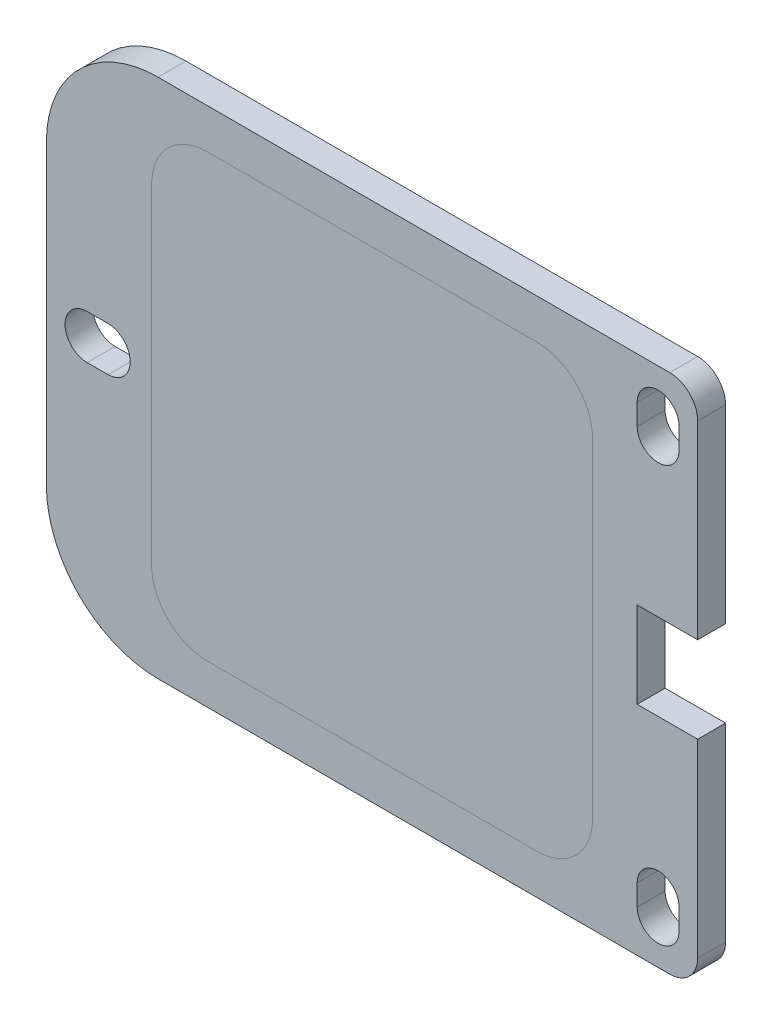
SolidWorks part; units mm, degrees
other "DetailItem1"
ref_plane "Front Plane" through (0, 0, 0) normal (0, 0, 1) x (1, 0, 0)
ref_plane "Top Plane" through (0, 0, 0) normal (0, 1, 0) x (1, 0, 0)
ref_plane "Right Plane" through (0, 0, 0) normal (1, 0, 0) x (0, 0, -1)
sketch "Sketch1" plane through (0, 0, 0) normal (0, 0, 1) x (1, 0, 0)
  line L0 (-222.25, 0) -> (180.975, 0) construction
  line L1 (-222.25, -177.8) -> (222.25, -177.8)
  line L2 (-222.25, -177.8) -> (-222.25, 177.8)
  line L3 (-222.25, 177.8) -> (222.25, 177.8)
  line L4 (222.25, -177.8) -> (222.25, -29.3687)
  line L5 (-222.25, -177.8) -> (222.25, 177.8) construction
  line L6 (-222.25, 177.8) -> (222.25, -177.8) construction
  line L7 (222.25, 29.3687) -> (180.975, 29.3687)
  line L8 (-194.4624, 0) -> (-180.1749, 0) construction
  line L9 (222.25, -29.3687) -> (180.975, -29.3687)
  line L10 (180.975, 29.3687) -> (180.975, -29.3687)
  line L11 (222.25, 29.3687) -> (222.25, 177.8)
  line L12 (-194.4624, 15.0812) -> (-180.1749, 15.0812)
  line L13 (-194.4624, -15.0812) -> (-180.1749, -15.0812)
  line L14 (195.2625, -134.9248) -> (195.2625, -149.225) construction
  line L15 (209.55, -134.9248) -> (209.55, -149.225)
  line L16 (180.975, -134.9248) -> (180.975, -149.225)
  line L17 (195.2625, 134.9248) -> (195.2625, 149.225) construction
  line L18 (209.55, 134.9248) -> (209.55, 149.225)
  line L19 (180.975, 134.9248) -> (180.975, 149.225)
  arc A0 (-194.4624, 15.0812) -> (-194.4624, -15.0812) centre (-194.4624, 0) ccw
  arc A1 (-180.1749, -15.0812) -> (-180.1749, 15.0812) centre (-180.1749, 0) ccw
  arc A2 (209.55, -134.9248) -> (180.975, -134.9248) centre (195.2625, -134.9248) ccw
  arc A3 (180.975, -149.225) -> (209.55, -149.225) centre (195.2625, -149.225) ccw
  arc A4 (209.55, 134.9248) -> (180.975, 134.9248) centre (195.2625, 134.9248) cw
  arc A5 (180.975, 149.225) -> (209.55, 149.225) centre (195.2625, 149.225) cw
  point P0 (0, 0)
  point P12 (180.975, 0)
  point P15 (-187.3186, 0)
  point P22 (195.2625, -142.0749)
  point P29 (195.2625, 142.0749)
  dimension "D5" = 15.0812
  dimension "D9" = 14.2875
  dimension "D1" = 355.6
  dimension "D2" = 444.5
  dimension "D3" = 58.7375
  dimension "D4" = 41.275
  dimension "D6" = 14.2875
  dimension "D7" = 27.7876
  dimension "D8" = 14.3002
  dimension "D10" = 12.7
  dimension "D11" = 28.575
extrude "Boss-Extrude1" add sketch "Sketch1" along normal blind 19.05
sketch "Sketch2" plane through (0, 0, 0) normal (0, 0, -1) x (-1, 0, 0)
  line L1 (-180.975, -134.9248) -> (-180.975, -149.225) construction
  line L2 (-180.975, 149.225) -> (-180.975, 134.9248) construction
  line L3 (180.1749, 15.0812) -> (194.4624, 15.0812) construction
  circle A0 centre (-195.2625, 142.0749) radius 25.4
  circle A1 centre (-195.2625, -142.0749) radius 25.4
  circle A2 centre (187.3186, 0) radius 25.4
  arc A3 (-180.975, -134.9248) -> (-209.55, -134.9248) centre (-195.2625, -134.9248) ccw construction
  arc A4 (-180.975, 149.225) -> (-209.55, 149.225) centre (-195.2625, 149.225) ccw construction
  arc A5 (194.4624, -15.0812) -> (194.4624, 15.0812) centre (194.4624, 0) ccw construction
  point P9 (-195.2625, -120.6373)
  point P12 (-180.975, -142.0749)
  point P16 (-195.2625, 163.5125)
  point P19 (-180.975, 142.0749)
  point P22 (187.3186, 15.0812)
  point P26 (209.5436, 0)
  dimension "D1" = 50.8
split line "Split Line1"
sketch "Sketch3" plane through (0, 0, 19.05) normal (0, 0, 1) x (1, 0, 0)
  line L1 (-112.395, -150.495) -> (112.395, -150.495)
  line L2 (-150.495, -112.395) -> (-150.495, 112.395)
  line L3 (-112.395, 150.495) -> (112.395, 150.495)
  line L4 (150.495, -112.395) -> (150.495, 112.395)
  line L5 (-150.495, -150.495) -> (150.495, 150.495) construction
  line L6 (-150.495, 150.495) -> (150.495, -150.495) construction
  arc A0 (112.395, -150.495) -> (150.495, -112.395) centre (112.395, -112.395) ccw
  arc A1 (112.395, 150.495) -> (150.495, 112.395) centre (112.395, 112.395) cw
  arc A2 (-150.495, 112.395) -> (-112.395, 150.495) centre (-112.395, 112.395) cw
  arc A3 (-112.395, -150.495) -> (-150.495, -112.395) centre (-112.395, -112.395) cw
  point P0 (0, 0)
  dimension "D2" = 38.1
  dimension "D3" = 38.1
  dimension "D1" = 300.99
split line "Split Line2"
fillet "Fillet1" radius 76.2 2 edges at (-222.25, 177.8, 9.525) (-222.25, -177.8, 9.525)
fillet "Fillet2" radius 19.05 2 edges at (222.25, 177.8, 9.525) (222.25, -177.8, 9.525)
